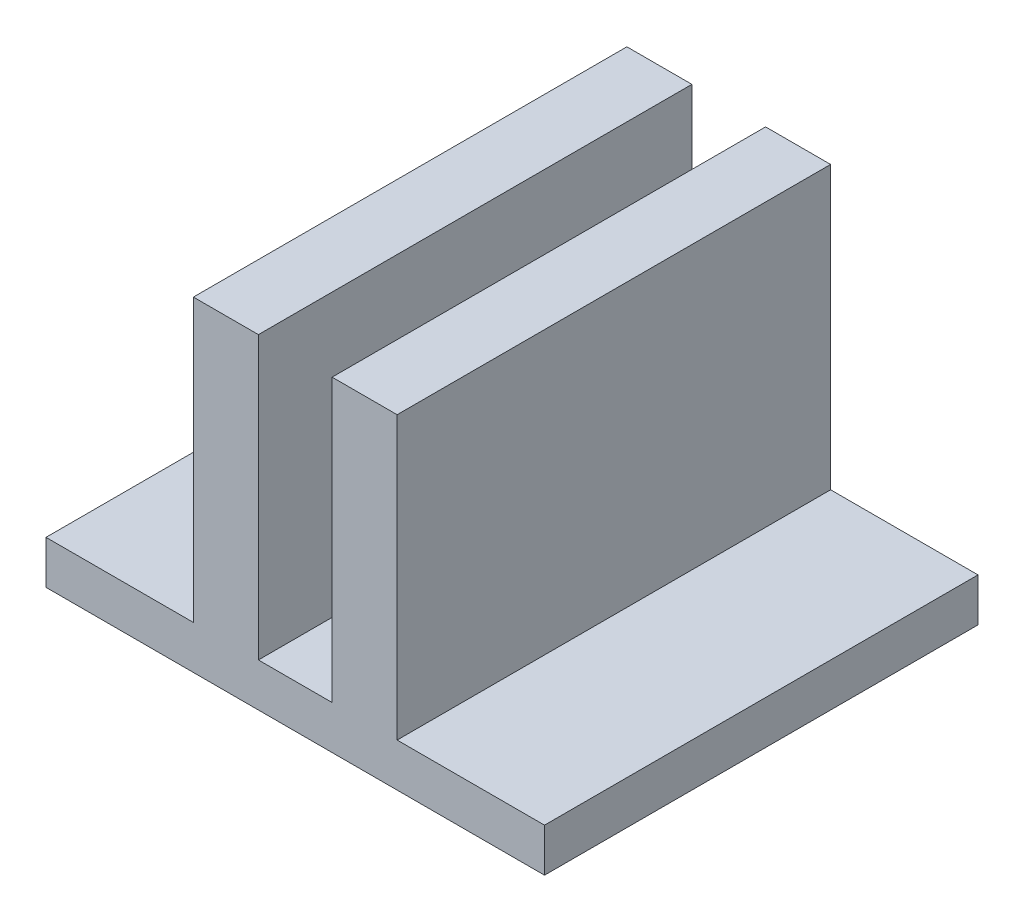
SolidWorks part; units mm, degrees
ref_plane "Plan de face" through (0, 0, 0) normal (0, 0, 1) x (1, 0, 0)
ref_plane "Plan de dessus" through (0, 0, 0) normal (0, 1, 0) x (1, 0, 0)
ref_plane "Plan de droite" through (0, 0, 0) normal (1, 0, 0) x (0, 0, -1)
sketch "Esquisse1" plane through (0, 0, 0) normal (0, 1, 0) x (1, 0, 0)
  line L0 (-8.3929, 11.1607) -> (4.6071, 11.1607)
  line L1 (-8.3929, 11.1607) -> (-8.3929, -8.8393)
  line L2 (4.6071, 11.1607) -> (4.6071, -8.8393)
  line L3 (4.6071, -8.8393) -> (-8.3929, -8.8393)
  dimension "D1" = 13
  dimension "D2" = 20
extrude "Boss.-Extru.1" add sketch "Esquisse1" along normal blind 15
sketch "Esquisse2" plane through (0, 15, 0) normal (0, 1, 0) x (1, 0, 0)
  line L0 (4.6071, 11.1607) -> (-8.3929, 11.1607) construction
  line L2 (-3.3929, 11.1607) -> (-0.3929, 11.1607)
  line L6 (-8.3929, -8.8393) -> (4.6071, -8.8393) construction
  line L7 (-3.3929, 11.1607) -> (-0.3929, 11.1607)
  line L8 (-3.3929, 11.1607) -> (-3.3929, -8.8393)
  line L9 (-3.3929, -8.8393) -> (-0.3929, -8.8393)
  line L10 (-0.3929, 11.1607) -> (-0.3929, -8.8393)
  line L12 (-8.3929, 11.1607) -> (-6.3929, 11.1607)
  line L13 (-8.3929, 11.1607) -> (-8.3929, -8.8393)
  line L14 (-8.3929, -8.8393) -> (-6.3929, -8.8393)
  line L15 (-6.3929, 11.1607) -> (-6.3929, -8.8393)
  line L16 (2.6071, 11.1607) -> (4.6071, 11.1607)
  line L17 (2.6071, 11.1607) -> (2.6071, -8.8393)
  line L18 (2.6071, -8.8393) -> (4.6071, -8.8393)
  line L19 (4.6071, 11.1607) -> (4.6071, -8.8393)
  point P0 (-3.3929, 11.1607)
  point P1 (-0.3929, 11.1607)
  point P7 (-6.3929, 11.1607)
  point P8 (2.6071, 11.1607)
  line M5 (-8.3929, 11.1607) -> (-8.3929, -8.8393)
  line M6 (-8.3929, -8.8393) -> (4.6071, -8.8393)
  line M7 (4.6071, -8.8393) -> (4.6071, 11.1607)
  line M8 (4.6071, 11.1607) -> (-8.3929, 11.1607)
  dimension "D1" = 5
  dimension "D2" = 5
  dimension "D3" = 3
  dimension "D4" = 3
extrude "Enlèv. mat.-Extru.2" cut sketch "Esquisse2" against normal blind 13 contours L15 M8 M5 M6 | L10 L8 M8 M6 | L17 M8 M6 M7
sketch "Esquisse4" plane through (-8.3929, 0, 0) normal (-1, 0, 0) x (0, 0, 1)
  line L4 (8.8393, 2) -> (-11.1607, 2)
  line L5 (-11.1607, 2) -> (-11.1607, 0)
  line L6 (-11.1607, 0) -> (8.8393, 0)
  line L7 (8.8393, 0) -> (8.8393, 2)
  line L8 (8.8393, 2) -> (-11.1607, 2)
  line L9 (-11.1607, 2) -> (-11.1607, 0)
  line L10 (-11.1607, 0) -> (8.8393, 0)
  line L11 (8.8393, 0) -> (8.8393, 2)
  dimension "D1" = 0
extrude "Boss.-Extru.2" add sketch "Esquisse4" along normal blind 5
sketch "Esquisse5" plane through (4.6071, 0, 0) normal (1, 0, 0) x (0, 0, -1)
  line L4 (11.1607, 2) -> (-8.8393, 2)
  line L5 (-8.8393, 2) -> (-8.8393, 0)
  line L6 (-8.8393, 0) -> (11.1607, 0)
  line L7 (11.1607, 0) -> (11.1607, 2)
  line L8 (11.1607, 2) -> (-8.8393, 2)
  line L9 (-8.8393, 2) -> (-8.8393, 0)
  line L10 (-8.8393, 0) -> (11.1607, 0)
  line L11 (11.1607, 0) -> (11.1607, 2)
  dimension "D1" = 0
extrude "Boss.-Extru.3" add sketch "Esquisse5" along normal blind 5
sketch "Esquisse6" plane through (-0.3929, 0, 0) normal (-1, 0, 0) x (0, 0, 1)
  line L4 (8.8393, 15) -> (-11.1607, 15)
  line L5 (-11.1607, 15) -> (-11.1607, 2)
  line L6 (-11.1607, 2) -> (8.8393, 2)
  line L7 (8.8393, 2) -> (8.8393, 15)
  line L8 (8.8393, 15) -> (-11.1607, 15)
  line L9 (-11.1607, 15) -> (-11.1607, 2)
  line L10 (-11.1607, 2) -> (8.8393, 2)
  line L11 (8.8393, 2) -> (8.8393, 15)
  dimension "D1" = 0
extrude "Enlèv. mat.-Extru.3" cut sketch "Esquisse6" against normal blind 0.2
sketch "Esquisse7" plane through (-3.3929, 0, 0) normal (1, 0, 0) x (0, 0, -1)
  line L4 (11.1607, 15) -> (-8.8393, 15)
  line L5 (-8.8393, 15) -> (-8.8393, 2)
  line L6 (-8.8393, 2) -> (11.1607, 2)
  line L7 (11.1607, 2) -> (11.1607, 15)
  line L8 (11.1607, 15) -> (-8.8393, 15)
  line L9 (-8.8393, 15) -> (-8.8393, 2)
  line L10 (-8.8393, 2) -> (11.1607, 2)
  line L11 (11.1607, 2) -> (11.1607, 15)
  dimension "D1" = 0
extrude "Enlèv. mat.-Extru.4" cut sketch "Esquisse7" against normal blind 0.2
sketch "Esquisse8" plane through (2.6071, 0, 0) normal (1, 0, 0) x (0, 0, -1)
  line L4 (11.1607, 15) -> (-8.8393, 15)
  line L5 (-8.8393, 15) -> (-8.8393, 2)
  line L6 (-8.8393, 2) -> (11.1607, 2)
  line L7 (11.1607, 2) -> (11.1607, 15)
  line L8 (11.1607, 15) -> (-8.8393, 15)
  line L9 (-8.8393, 15) -> (-8.8393, 2)
  line L10 (-8.8393, 2) -> (11.1607, 2)
  line L11 (11.1607, 2) -> (11.1607, 15)
  dimension "D1" = 0
extrude "Boss.-Extru.4" add sketch "Esquisse8" along normal blind 0.2
sketch "Esquisse9" plane through (-6.3929, 0, 0) normal (-1, 0, 0) x (0, 0, 1)
  line L4 (8.8393, 15) -> (-11.1607, 15)
  line L5 (-11.1607, 15) -> (-11.1607, 2)
  line L6 (-11.1607, 2) -> (8.8393, 2)
  line L7 (8.8393, 2) -> (8.8393, 15)
  line L8 (8.8393, 15) -> (-11.1607, 15)
  line L9 (-11.1607, 15) -> (-11.1607, 2)
  line L10 (-11.1607, 2) -> (8.8393, 2)
  line L11 (8.8393, 2) -> (8.8393, 15)
  dimension "D1" = 0
extrude "Boss.-Extru.5" add sketch "Esquisse9" along normal blind 0.2
